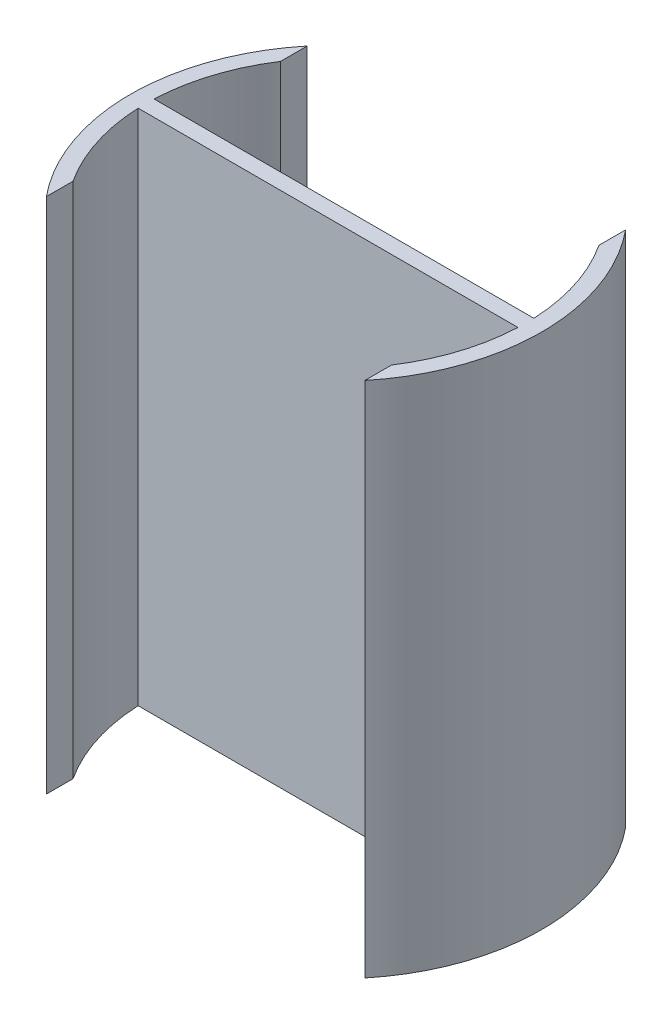
SolidWorks part; units mm, degrees
ref_plane "Front Plane" through (0, 0, 0) normal (0, 0, 1) x (1, 0, 0)
ref_plane "Top Plane" through (0, 0, 0) normal (0, 1, 0) x (1, 0, 0)
ref_plane "Right Plane" through (0, 0, 0) normal (1, 0, 0) x (0, 0, -1)
sketch "Sketch2" plane through (0, 0, 0) normal (0, 1, 0) x (1, 0, 0)
  circle A0 centre (0, 0) radius 25.85
  dimension "D1" = 51.7
extrude "Boss-Extrude1" add sketch "Sketch2" along normal blind 65
sketch "Sketch4" plane through (0, 65, 0) normal (0, 1, 0) x (1, 0, 0)
  line L0 (-25.85, 0) -> (25.85, 0) construction
  line L1 (-25.85, 0) -> (-23.85, 0) construction
  line L2 (25.85, 0) -> (23.85, 0) construction
  line L3 (-23.85, 1) -> (23.85, 1)
  line L4 (-23.85, 1) -> (23.85, 1) construction
  line L5 (-23.85, 1) -> (-23.85, -1) construction
  line L6 (-23.85, -1) -> (23.85, -1) construction
  line L7 (23.85, 1) -> (23.85, -1) construction
  line L8 (-23.85, 1) -> (23.85, -1) construction
  line L9 (-23.85, -1) -> (23.85, 1) construction
  line L10 (23.85, -1) -> (-23.85, -1)
  line L12 (-20, 36.371) -> (20, 36.371)
  line L13 (-20, 36.371) -> (-20, 11.371)
  line L14 (-20, 11.371) -> (20, 11.371)
  line L15 (20, 36.371) -> (20, 11.371)
  line L16 (-20, 36.371) -> (20, 11.371) construction
  line L17 (-20, 11.371) -> (20, 36.371) construction
  line L18 (-20, -11.371) -> (20, -11.371)
  line L19 (-20, -11.371) -> (-20, -36.371)
  line L20 (-20, -36.371) -> (20, -36.371)
  line L21 (20, -11.371) -> (20, -36.371)
  line L22 (-20, -11.371) -> (20, -36.371) construction
  line L23 (-20, -36.371) -> (20, -11.371) construction
  circle A0 centre (0, 0) radius 25.85 construction
  arc A1 (-23.85, 1) -> (23.85, 1) centre (0, 0) cw
  arc A2 (23.85, -1) -> (-23.85, -1) centre (0, 0) cw
  point P5 (0, 0)
  point P16 (0, 23.871)
  point P21 (0, -23.871)
  circle M4 centre (0, 0) radius 25.85
  dimension "D1" = 2
  dimension "D2" = 25
  dimension "D3" = 40
extrude "Cut-Extrude1" cut sketch "Sketch4" against normal blind 100 contours L13 A1 L15 M4 | A1 L13 L14 L15 | A1 L3 L15 L14 L13 | A2 L19 L18 L21 L10 | A2 L21 L18 L19 | L21 A2 L19 M4
sketch "Sketch5" plane through (0, 0, 0) normal (0, -1, 0) x (1, 0, 0)
  line L1 (-23.85, 1) -> (23.85, 1)
  line L2 (-23.85, 1) -> (-23.85, -1)
  line L3 (-23.85, -1) -> (23.85, -1)
  line L4 (23.85, 1) -> (23.85, -1)
